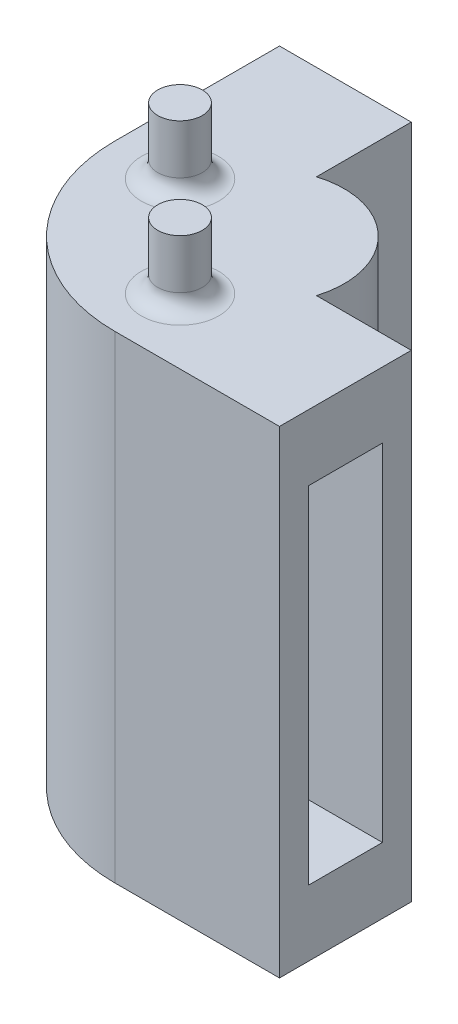
SolidWorks part; units mm, degrees
ref_plane "Front Plane" through (0, 0, 0) normal (0, 0, 1) x (1, 0, 0)
ref_plane "Top Plane" through (0, 0, 0) normal (0, 1, 0) x (1, 0, 0)
ref_plane "Right Plane" through (0, 0, 0) normal (1, 0, 0) x (0, 0, -1)
sketch "Sketch2" plane through (0, 0, 0) normal (0, 1, 0) x (1, 0, 0)
  line L0 (0, 10) -> (0, 20)
  line L1 (0, 20) -> (8, 20)
  line L2 (8, 20) -> (8, 14.2452)
  line L3 (0, 0) -> (22.3158, 22.3158) construction
  line L4 (10, 0) -> (22.3158, 0) construction
  line L5 (18, 8) -> (22.3158, 8) construction
  line L6 (2.9289, 2.9289) -> (9.4645, 9.4645)
  line L7 (9.4645, 9.4645) -> (13, 13)
  arc A0 (2.9289, 2.9289) -> (0, 10) centre (10, 10) cw
  arc A2 (13, 13) -> (8, 14.2452) centre (9.4645, 9.4645) ccw
  point P13 (8, 8)
  dimension "D2" = 10
  dimension "D5" = 10
  dimension "D1" = 8
  dimension "D4" = 20
other "AlignGroup1"
extrude "Boss-Extrude1" add sketch "Sketch2" along normal blind 29
ref_plane "Plane1" through (0, 0, 0) normal (0.7071, 0, 0.7071) x (0.7071, 0, -0.7071)
mirror "Mirror1" about plane through (0, 0, 0) normal (0.7071, 0, 0.7071) of "Boss-Extrude1"
sketch "Sketch3" plane through (0, 0, -20) normal (0, 0, -1) x (-1, 0, 0)
  line L0 (-4, 0) -> (-4, 4) construction
  line L2 (-8, 0) -> (0, 0) construction
  line L3 (-6.25, 4) -> (-6.25, 25)
  line L4 (-6.25, 4) -> (-1.75, 4)
  line L5 (-6.25, 14.5) -> (-1.75, 14.5) construction
  line L6 (-6.25, 25) -> (-1.75, 25)
  line L7 (-1.75, 4) -> (-1.75, 25)
  dimension "D1" = 4
  dimension "D2" = 4.5
extrude "Cut-Extrude1" cut sketch "Sketch3" against normal blind 6
mirror "Mirror2" about plane through (0, 0, 0) normal (0.7071, 0, 0.7071) of "Cut-Extrude1"
sketch "Sketch5" plane through (0, 29, 0) normal (0, 1, 0) x (1, 0, 0)
  line L0 (2.9289, 2.9289) -> (10, 10) construction
  circle A0 centre (9.9991, 3.9621) radius 1.35
  arc A1 (0, 10) -> (10, 0) centre (10, 10) ccw construction
  circle A2 centre (3.9621, 9.9991) radius 1.35
extrude "Boss-Extrude2" add sketch "Sketch5" along normal blind 4
fillet "Fillet1" radius 1 2 edges at (3.9621, 29, -11.3491) (9.9991, 29, -2.6121)
